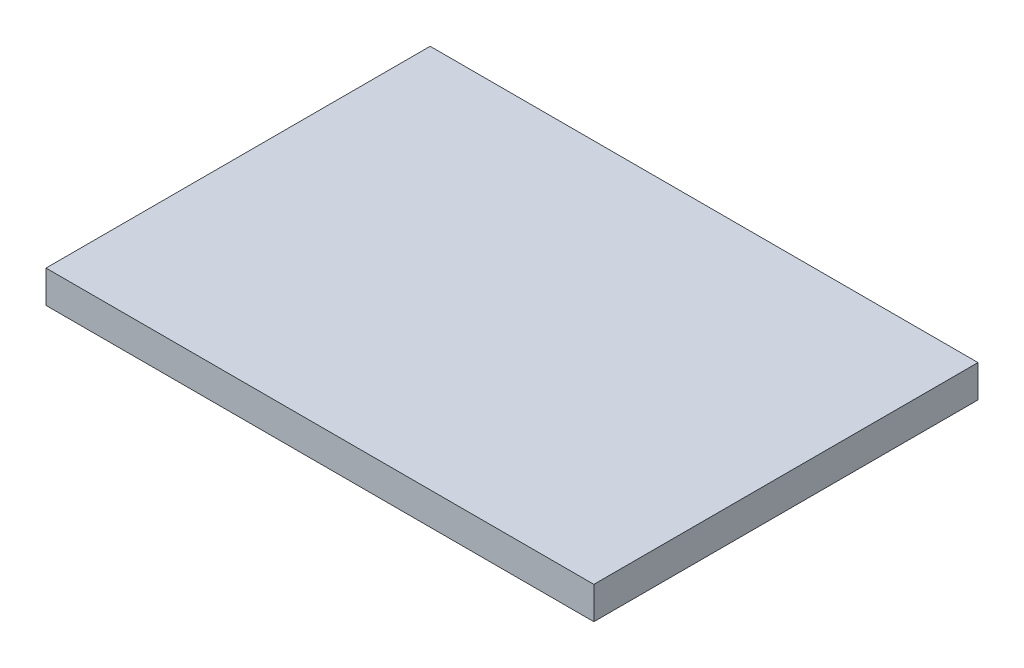
SolidWorks part; units mm, degrees
ref_plane "Front Plane" through (0, 0, 0) normal (0, 0, 1) x (1, 0, 0)
ref_plane "Top Plane" through (0, 0, 0) normal (0, 1, 0) x (1, 0, 0)
ref_plane "Right Plane" through (0, 0, 0) normal (1, 0, 0) x (0, 0, -1)
sketch "Sketch1" plane through (0, 0, 0) normal (0, 0, 1) x (1, 0, 0)
  line L1 (161.15, -14.05) -> (161.15, -33.1)
  line L2 (100.1317, -14.05) -> (-100.1317, -14.05) construction
  line L4 (-161.15, -14.05) -> (-161.15, -33.1)
  line L5 (100.1317, -14.05) -> (-100.1317, -14.05)
  line L7 (100.1317, -14.05) -> (161.15, -14.05)
  line L9 (-100.1317, -14.05) -> (-161.15, -14.05)
  line L11 (-161.15, -33.1) -> (161.15, -33.1)
extrude "Boss-Extrude1" add sketch "Sketch1" along normal up to surface (226 mm away)
